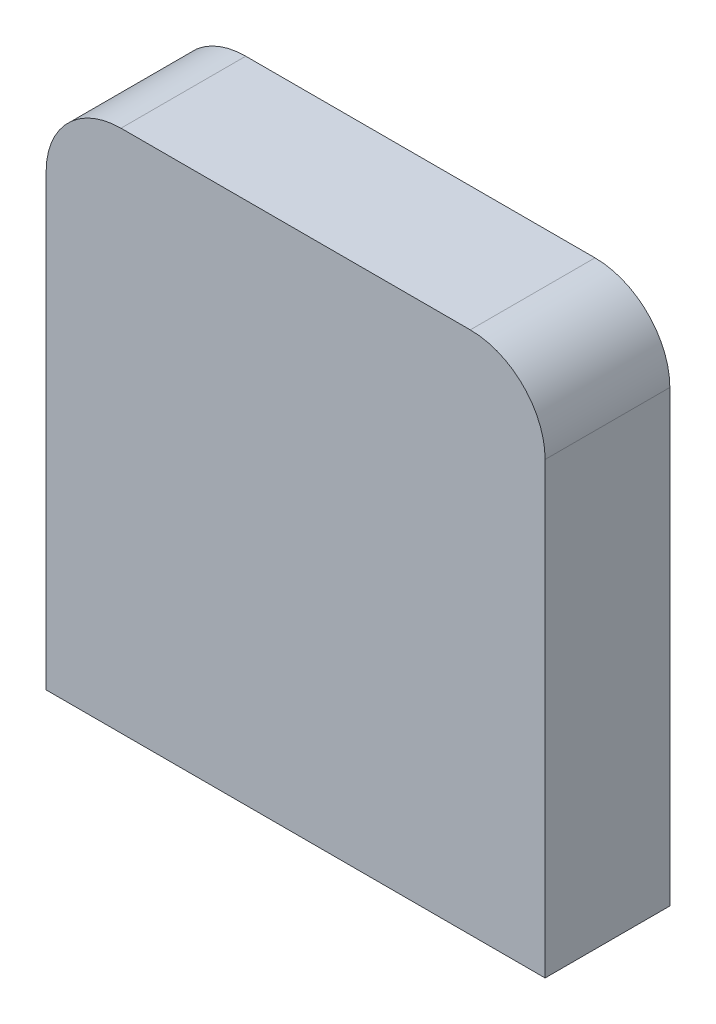
SolidWorks part; units mm, degrees
ref_plane "前基準面" through (0, 0, 0) normal (0, 0, 1) x (1, 0, 0)
ref_plane "上基準面" through (0, 0, 0) normal (0, 1, 0) x (1, 0, 0)
ref_plane "右基準面" through (0, 0, 0) normal (1, 0, 0) x (0, 0, -1)
sketch "草圖1" plane through (0, 0, 0) normal (0, 0, 1) x (1, 0, 0)
  line L1 (-7, 10.5) -> (7, 10.5)
  line L2 (-10, 7.5) -> (-10, -10.5)
  line L3 (-10, -10.5) -> (10, -10.5)
  line L4 (10, 7.5) -> (10, -10.5)
  line L5 (-10, 10.5) -> (10, -10.5) construction
  line L6 (-10, -10.5) -> (10, 10.5) construction
  arc A0 (7, 10.5) -> (10, 7.5) centre (7, 7.5) cw
  arc A1 (-7, 10.5) -> (-10, 7.5) centre (-7, 7.5) ccw
  point P0 (0, 0)
  dimension "D3" = 3
  dimension "D1" = 20
  dimension "D2" = 21
extrude "填料-伸長1" add sketch "草圖1" along normal blind 5
